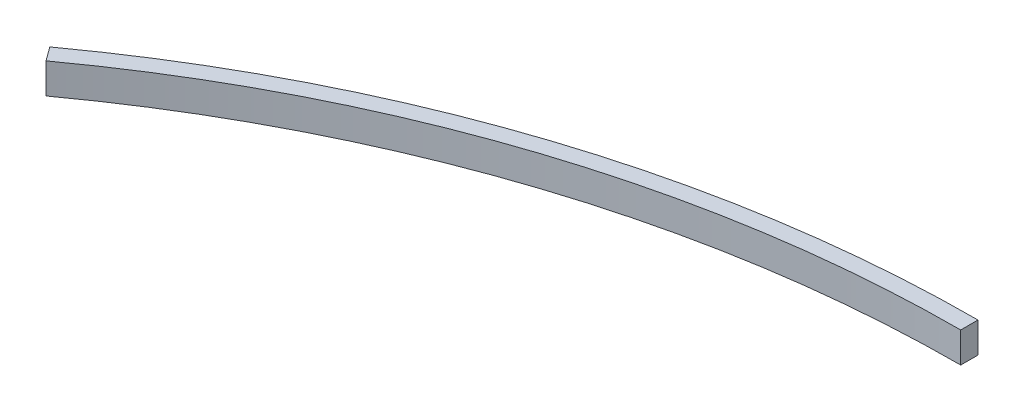
SolidWorks part; units mm, degrees
ref_plane "Front Plane" through (0, 0, 0) normal (0, 0, 1) x (1, 0, 0)
ref_plane "Top Plane" through (0, 0, 0) normal (0, 1, 0) x (1, 0, 0)
ref_plane "Right Plane" through (0, 0, 0) normal (1, 0, 0) x (0, 0, -1)
sketch "Sketch1" plane through (0, 0, 0) normal (0, 1, 0) x (1, 0, 0)
  line L0 (0, 0) -> (0, 150.2293) construction
  line L1 (0, 0) -> (-95.8472, 131.9224) construction
  line L2 (-64.3845, 88.6177) -> (-63.4514, 87.3334)
  line L3 (0, 109.5375) -> (0, 107.95)
  arc A0 (0, 107.95) -> (-63.4514, 87.3334) centre (0, 0) ccw
  arc A1 (0, 109.5375) -> (-64.3845, 88.6177) centre (0, 0) ccw
  dimension "D1" = 215.9
  dimension "D2" = 1.5875
  dimension "D3" = 36
extrude "Boss-Extrude1" add sketch "Sketch1" along normal blind 2.794
